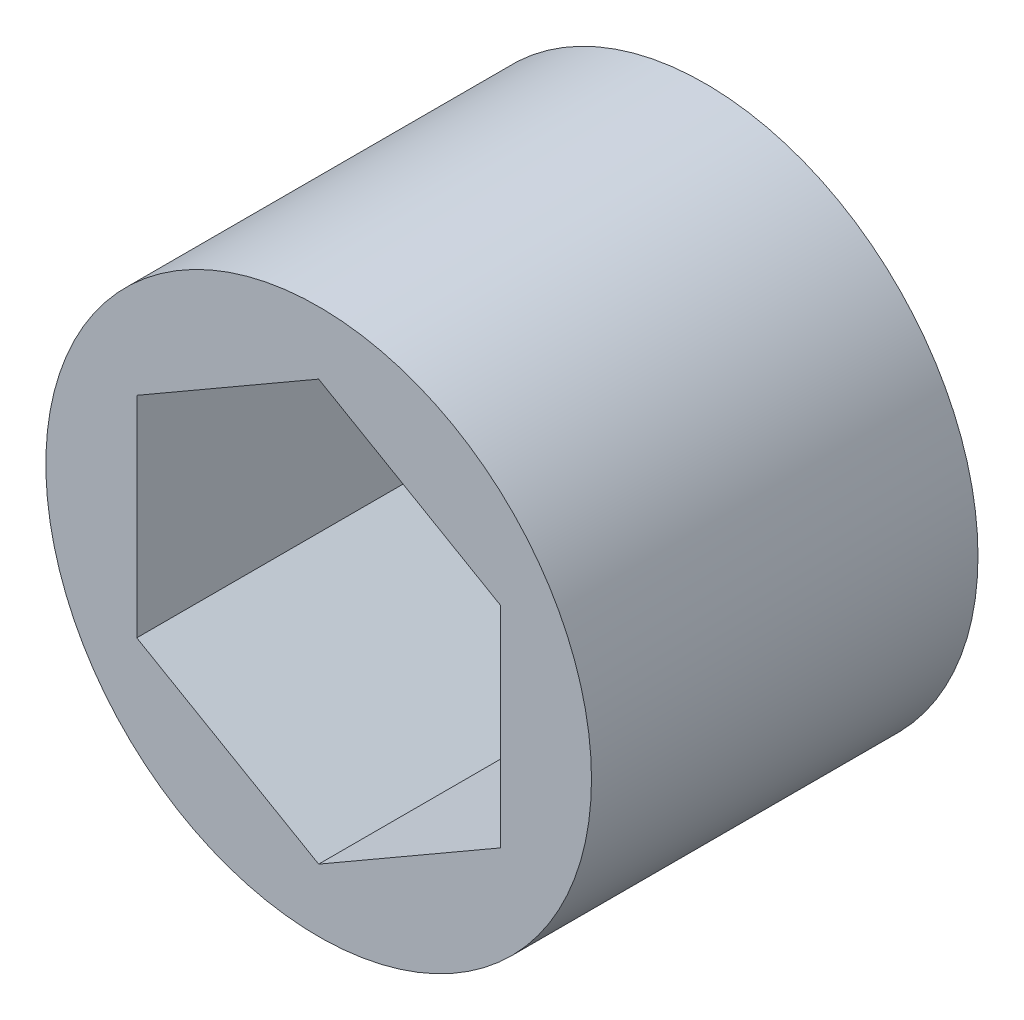
SolidWorks part; units mm, degrees
ref_plane "Front Plane" through (0, 0, 0) normal (0, 0, 1) x (1, 0, 0)
ref_plane "Top Plane" through (0, 0, 0) normal (0, 1, 0) x (1, 0, 0)
ref_plane "Right Plane" through (0, 0, 0) normal (1, 0, 0) x (0, 0, -1)
sketch "Sketch1" plane through (0, 0, 0) normal (0, 0, 1) x (1, 0, 0)
  line L1 (0, 7.3323) -> (-6.35, 3.6662)
  line L2 (-6.35, 3.6662) -> (-6.35, -3.6662)
  line L3 (-6.35, -3.6662) -> (0, -7.3323)
  line L4 (0, -7.3323) -> (6.35, -3.6662)
  line L5 (6.35, -3.6662) -> (6.35, 3.6662)
  line L6 (6.35, 3.6662) -> (0, 7.3323)
  circle A0 centre (0, 0) radius 9.525
  circle A1 centre (0, 0) radius 6.35 construction
  dimension "D1" = 19.05
  dimension "D2" = 12.7
extrude "Boss-Extrude1" add sketch "Sketch1" along normal mid plane 13.4937
